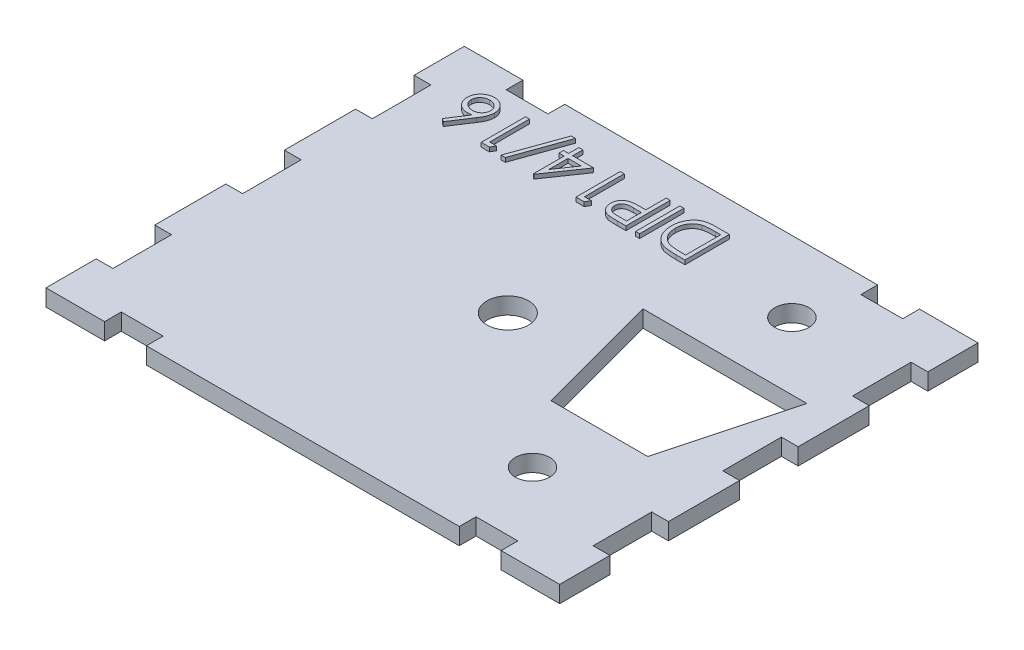
SolidWorks part; units mm, degrees
ref_plane "Front Plane" through (0, 0, 0) normal (0, 0, 1) x (1, 0, 0)
ref_plane "Top Plane" through (0, 0, 0) normal (0, 1, 0) x (1, 0, 0)
ref_plane "Right Plane" through (0, 0, 0) normal (1, 0, 0) x (0, 0, -1)
sketch "Sketch2" plane through (0, 0, 0) normal (0, 1, 0) x (1, 0, 0)
  line L1 (-50, 25) -> (50, 25)
  line L2 (-50, 25) -> (-50, -25)
  line L3 (-50, -25) -> (50, -25)
  line L4 (50, 25) -> (50, -25)
  line L5 (-50, 25) -> (50, -25) construction
  line L6 (-50, -25) -> (50, 25) construction
  point P0 (0, 0)
  dimension "D1" = 100
  dimension "D2" = 50
extrude "Boss-Extrude1" add sketch "Sketch2" along normal blind 2
sketch "Sketch12" plane through (0, 2, 0) normal (0, 1, 0) x (1, 0, 0)
  line L0 (-50, -25) -> (50, -25) construction
  line L1 (-40.2, -25) -> (-50, -25)
  line L2 (-40.2, -25) -> (-40.2, 25)
  line L3 (-40.2, 25) -> (-50, 25)
  line L4 (-50, -25) -> (-50, 25)
  line L5 (-50, -25) -> (50, -25) construction
  line L6 (41.2, -25) -> (50, -25)
  line L7 (41.2, -25) -> (41.2, 25)
  line L8 (41.2, 25) -> (50, 25)
  line L9 (50, -25) -> (50, 25)
extrude "Cut-Extrude8" cut sketch "Sketch12" against normal blind 6
sketch "Sketch13" plane through (0, 2, 0) normal (0, 1, 0) x (1, 0, 0)
  line L1 (-28.2, 19) -> (-30.2, 19)
  line L2 (-28.2, 19) -> (-28.2, 12)
  line L3 (-28.2, 12) -> (-30.2, 12)
  line L4 (-30.2, 19) -> (-30.2, 12)
  line L5 (-28.2, 3.5) -> (-30.2, 3.5)
  line L6 (-28.2, 3.5) -> (-28.2, -3.5)
  line L7 (-28.2, -3.5) -> (-30.2, -3.5)
  line L8 (-30.2, 3.5) -> (-30.2, -3.5)
  line L9 (-28.2, -12) -> (-30.2, -12)
  line L10 (-28.2, -12) -> (-28.2, -19)
  line L11 (-28.2, -19) -> (-30.2, -19)
  line L12 (-30.2, -12) -> (-30.2, -19)
  line L13 (29.2, 19) -> (31.2, 19)
  line L14 (29.2, 19) -> (29.2, 12)
  line L15 (29.2, 12) -> (31.2, 12)
  line L16 (31.2, 19) -> (31.2, 12)
  line L17 (29.2, 3.5) -> (31.2, 3.5)
  line L18 (29.2, 3.5) -> (29.2, -3.5)
  line L19 (29.2, -3.5) -> (31.2, -3.5)
  line L20 (31.2, 3.5) -> (31.2, -3.5)
  line L21 (29.2, -12) -> (31.2, -12)
  line L22 (29.2, -12) -> (29.2, -19)
  line L23 (29.2, -19) -> (31.2, -19)
  line L24 (31.2, -12) -> (31.2, -19)
  line L25 (-40.2, -25) -> (41.2, -25) construction
  line L26 (-23.2, 25) -> (-18.2, 25)
  line L27 (41.2, 25) -> (-40.2, 25) construction
  line L28 (-40.2, -25) -> (41.2, -25) construction
  line L29 (41.2, 25) -> (-40.2, 25) construction
  line L30 (-40.2, -25) -> (41.2, -25) construction
  line L31 (41.2, 25) -> (31.2, 25)
  line L32 (41.2, 25) -> (41.2, -25)
  line L33 (41.2, -25) -> (31.2, -25)
  line L34 (31.2, 25) -> (31.2, -25)
  line L35 (41.2, 25) -> (-40.2, 25) construction
  line L36 (-40.2, -25) -> (-30.2, -25)
  line L37 (-40.2, -25) -> (-40.2, 25)
  line L38 (-40.2, 25) -> (-30.2, 25)
  line L39 (-30.2, -25) -> (-30.2, 25)
  line L40 (-23.2, 25) -> (-23.2, 23)
  line L41 (-23.2, 23) -> (-18.2, 23)
  line L42 (-18.2, 25) -> (-18.2, 23)
  line L43 (-23.2, -25) -> (-18.2, -25)
  line L44 (-23.2, -25) -> (-23.2, -23)
  line L45 (-23.2, -23) -> (-18.2, -23)
  line L46 (-18.2, -25) -> (-18.2, -23)
  line L47 (24.2, -25) -> (19.2, -25)
  line L48 (24.2, -25) -> (24.2, -23)
  line L49 (24.2, -23) -> (19.2, -23)
  line L50 (19.2, -25) -> (19.2, -23)
  line L51 (24.2, 25) -> (19.2, 25)
  line L52 (24.2, 25) -> (24.2, 23)
  line L53 (24.2, 23) -> (19.2, 23)
  line L54 (19.2, 25) -> (19.2, 23)
  point P24 (29.2, 0)
  point P30 (30.2, 3.5)
  line M32 (41.2, -25) -> (41.2, 25)
  line M41 (41.2, 25) -> (-40.2, 25)
  line M42 (-40.2, 25) -> (-40.2, -25)
  line M47 (-40.2, -25) -> (41.2, -25)
  dimension "D1" = 2
  dimension "D2" = 2
  dimension "D3" = 2
  dimension "D4" = 2
  dimension "D5" = 2
  dimension "D6" = 2
  dimension "D7" = 57.4
  dimension "D8" = 57.4
  dimension "D9" = 57.4
  dimension "D10" = 7
  dimension "D11" = 7
  dimension "D12" = 7
  dimension "D13" = 7
  dimension "D14" = 7
  dimension "D15" = 7
  dimension "D16" = 5
  dimension "D17" = 2
  dimension "D18" = 5
  dimension "D19" = 6
  dimension "D20" = 8.5
  dimension "D21" = 8.5
  dimension "D22" = 6
  dimension "D23" = 6
  dimension "D24" = 8.5
  dimension "D25" = 8.5
  dimension "D26" = 6
  dimension "D27" = 5
  dimension "D28" = 5
  dimension "D29" = 2
  dimension "D30" = 2
  dimension "D31" = 5
  dimension "D32" = 5
  dimension "D33" = 5
  dimension "D34" = 5
  dimension "D35" = 2
extrude "Cut-Extrude10" cut sketch "Sketch13" against normal blind 6 contours L5 L8 L7 L6 | L39 L12 L8 L4 M47 M41 M42 | L1 L4 L3 L2 | L50 L48 L49 M47 | L24 L21 L22 L23 | L20 L17 L18 L19 | L16 L13 L14 L15 | L54 L53 L52 M41 | L9 L12 L11 L10 | L34 L16 L20 L24 M41 M47 M32 | L26 L42 L41 L40 | L45 L46 L43 L44
sketch "Sketch15" plane through (0, 0, 0) normal (0, -1, 0) x (1, 0, 0)
  line L0 (24.2, 23) -> (19.2, 23) construction
  line L16 (20.7242, -7.5) -> (20.7242, -8.5)
  line L17 (20.7242, -7.5) -> (25.936, -7.5)
  line L18 (25.936, -7.5) -> (22.4527, 5.5)
  line L19 (22.4527, 5.5) -> (12.4527, 5.5)
  line L20 (12.4527, 5.5) -> (8.9693, -7.5)
  line L21 (8.9693, -7.5) -> (14.1811, -7.5)
  line L22 (14.1811, -7.5) -> (14.1811, -8.5)
  line L23 (14.1811, -8.5) -> (7.6661, -8.5)
  line L24 (7.6661, -8.5) -> (11.6853, 6.5)
  line L25 (11.6853, 6.5) -> (23.22, 6.5)
  line L26 (23.22, 6.5) -> (27.2392, -8.5)
  line L27 (27.2392, -8.5) -> (20.7242, -8.5)
  line L28 (20.7242, -8.5) -> (14.1811, -8.5)
  line L29 (14.1811, -7.5) -> (20.7242, -7.5)
  line L31 (29.2, 12) -> (29.2, 19) construction
  dimension "D4" = 16.5
  dimension "D18" = 11.5347
  dimension "D19" = 15.5291
  dimension "D20" = 15.5291
  dimension "D21" = 13.4586
  dimension "D22" = 13.4586
  dimension "D23" = 10
  dimension "D24" = 5.2118
  dimension "D25" = 5.2118
  dimension "D26" = 6.515
  dimension "D27" = 6.515
  dimension "D28" = 1
  dimension "D29" = 105
  dimension "D30" = 105
  dimension "D31" = 75
  dimension "D32" = 75
  dimension "D33" = 5.98
  dimension "D34" = 1
extrude "Cut-Extrude13" cut sketch "Sketch15" against normal blind 10 contours L21 L29 L17 L18 L19 L20 | L27 L26 L25 L24 L23 L22 L21 L20 L19 L18 L17 L16 | L29 L22 L28 L16
sketch "Sketch16" plane through (0, 0, 0) normal (0, -1, 0) x (-1, 0, 0)
  circle A0 centre (0, 0) radius 2.5
  dimension "D1" = 5
extrude "Cut-Extrude14" cut sketch "Sketch16" against normal blind 10 contours A0
sketch "Sketch17" plane through (0, 0, 0) normal (0, -1, 0) x (-1, 0, 0)
  line L2 (-27.2392, 8.5) -> (-7.6661, 8.5) construction
  line L4 (-11.6853, -6.5) -> (-23.22, -6.5) construction
  circle A0 centre (-17.4527, -14.5) radius 2.05
  circle A1 centre (-17.4527, 16.5) radius 2.05
  dimension "D1" = 4.1
  dimension "D2" = 4.1
  dimension "D3" = 8
  dimension "D4" = 9.7866
  dimension "D5" = 9.7866
  dimension "D6" = 5.7673
  dimension "D7" = 5.7673
  dimension "D8" = 8
extrude "Cut-Extrude15" cut sketch "Sketch17" against normal blind 3.5
sketch "Sketch22" plane through (0, 2, 0) normal (0, 1, 0) x (1, 0, 0)
  line L0 (-24.5837, 20.8621) -> (9.284, 20.8621) construction
  text T0 "DIP14/16" font "Century Gothic" height in points 20
extrude "Boss-Extrude4" add sketch "Sketch22" along normal blind 0.5
